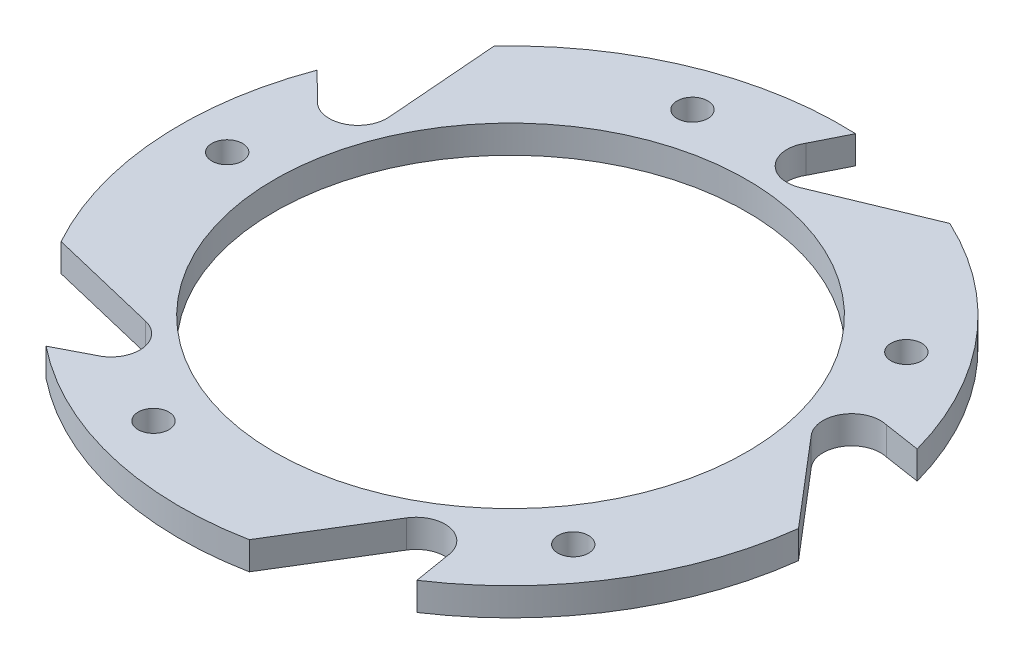
SolidWorks part; units mm, degrees
ref_plane "Front Plane" through (0, 0, 0) normal (0, 0, 1) x (1, 0, 0)
ref_plane "Top Plane" through (0, 0, 0) normal (0, 1, 0) x (1, 0, 0)
ref_plane "Right Plane" through (0, 0, 0) normal (1, 0, 0) x (0, 0, -1)
sketch "Sketch1" plane through (0, 0, 0) normal (0, 1, 0) x (1, 0, 0)
  line L0 (0, 0) -> (-60.96, 0) construction
  line L1 (0, 0) -> (-56.2704, 23.447) construction
  line L2 (-60.96, 19.4126) -> (-66.5913, 24.973)
  line L3 (-50.1033, 23.9311) -> (-52.0306, 48.4858)
  line L4 (-0.3752, 63.9752) -> (3.1729, 71.0492)
  line L5 (7.277, 55.0461) -> (30.0343, 64.467)
  line L6 (60.7281, 20.1263) -> (68.5523, 18.9378)
  line L7 (54.6007, 10.0893) -> (70.5929, -8.643)
  line L8 (37.9072, -51.5365) -> (39.1948, -59.345)
  line L9 (26.4681, -48.8106) -> (13.5944, -69.8086)
  line L10 (-37.3002, -51.9776) -> (-44.3286, -55.615)
  line L11 (-38.2425, -40.2559) -> (-62.191, -34.5011)
  circle A0 centre (0, 0) radius 71.12
  circle A1 centre (0, 0) radius 50.8
  circle A2 centre (-60.96, 0) radius 3.3
  circle A3 centre (-18.8377, 57.9764) radius 3.3
  circle A4 centre (49.3177, 35.8314) radius 3.3
  circle A5 centre (49.3177, -35.8314) radius 3.3
  circle A6 centre (-18.8377, -57.9764) radius 3.3
  circle A7 centre (-56.2704, 23.447) radius 6.1861
  circle A8 centre (4.9109, 60.7619) radius 6.1861
  circle A9 centre (59.3055, 14.1059) radius 6.1861
  circle A10 centre (31.7419, -52.0439) radius 6.1861
  circle A11 centre (-39.6879, -46.2708) radius 6.1861
  point P16 (0, 0)
  point P48 (0, 0)
  dimension "D2" = 5
  dimension "D1" = 5
extrude "Boss-Extrude1" add sketch "Sketch1" along normal blind 6 contours A0 A6 A5 A4 A3 A2 A1
